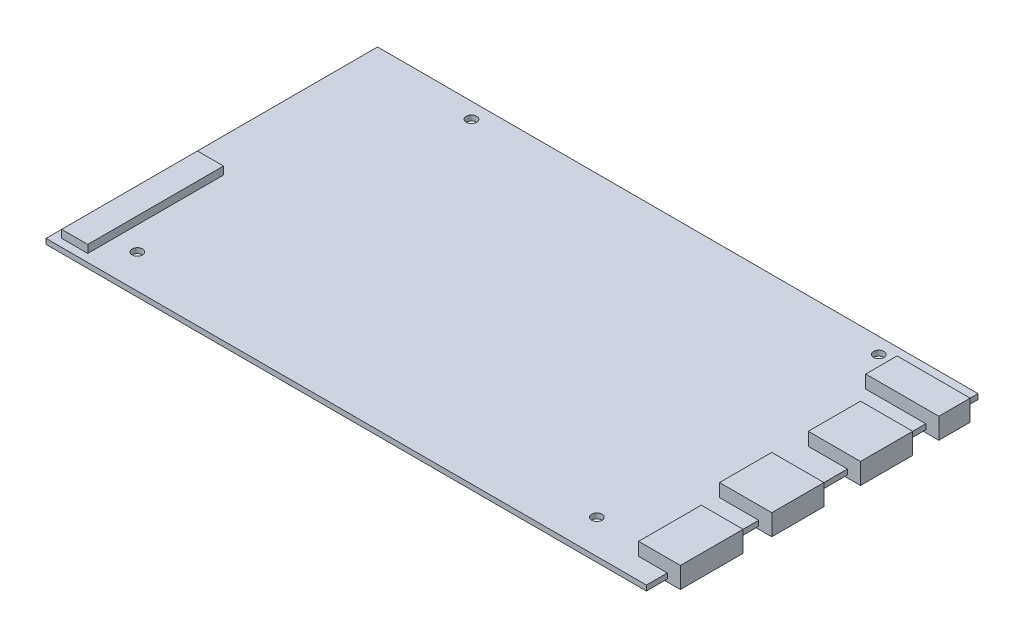
SolidWorks part; units mm, degrees
ref_plane "Front Plane" through (0, 0, 0) normal (0, 0, 1) x (1, 0, 0)
ref_plane "Top Plane" through (0, 0, 0) normal (0, 1, 0) x (1, 0, 0)
ref_plane "Right Plane" through (0, 0, 0) normal (1, 0, 0) x (0, 0, -1)
sketch "Sketch1" plane through (0, 0, 0) normal (0, 1, 0) x (1, 0, 0)
  line L1 (-57.5, 31.75) -> (57.5, 31.75)
  line L2 (-57.5, 31.75) -> (-57.5, -31.75)
  line L3 (-57.5, -31.75) -> (57.5, -31.75)
  line L4 (57.5, 31.75) -> (57.5, -31.75)
  line L5 (-57.5, 31.75) -> (57.5, -31.75) construction
  line L6 (-57.5, -31.75) -> (57.5, 31.75) construction
  circle A0 centre (-46.5, -25.25) radius 1
  circle A1 centre (-36.5, 28.75) radius 1
  circle A2 centre (41.5, 28.75) radius 1
  circle A3 centre (41.5, -25.25) radius 1
  point P0 (0, 0)
  dimension "D3" = 2
  dimension "D1" = 115
  dimension "D2" = 63.5
  dimension "D4" = 54
  dimension "D5" = 78
  dimension "D6" = 88
  dimension "D7" = 21
  dimension "D8" = 16
  dimension "D9" = 3
extrude "PCB" add sketch "Sketch1" along normal blind 1
sketch "Sketch2" plane through (0, 0, 0) normal (0, 1, 0) x (1, 0, 0)
  line L0 (-57.5, -31.75) -> (57.5, -31.75) construction
  line L1 (60, -27.75) -> (52, -27.75)
  line L2 (60, -27.75) -> (60, -15.75)
  line L3 (60, -15.75) -> (52, -15.75)
  line L4 (52, -27.75) -> (52, -15.75)
  line L5 (60, -10.25) -> (50, -10.25)
  line L6 (60, -10.25) -> (60, -0.25)
  line L7 (60, -0.25) -> (50, -0.25)
  line L8 (50, -10.25) -> (50, -0.25)
  line L9 (60, 6.75) -> (50, 6.75)
  line L10 (60, 6.75) -> (60, 16.75)
  line L11 (60, 16.75) -> (50, 16.75)
  line L12 (50, 6.75) -> (50, 16.75)
  line L13 (60, 27.75) -> (46, 27.75)
  line L14 (60, 27.75) -> (60, 21.75)
  line L15 (60, 21.75) -> (46, 21.75)
  line L16 (46, 27.75) -> (46, 21.75)
  line L17 (57.5, -31.75) -> (57.5, 31.75) construction
  line L18 (57.5, 31.75) -> (-57.5, 31.75) construction
  dimension "D1" = 4
  dimension "D2" = 16
  dimension "D3" = 2.5
  dimension "D4" = 8
  dimension "D5" = 21.5
  dimension "D6" = 31.5
  dimension "D7" = 10
  dimension "D8" = 25
  dimension "D9" = 15
  dimension "D10" = 4
  dimension "D11" = 10
  dimension "D12" = 14
extrude "CONNECTORS" add sketch "Sketch2" along normal blind 3.5 and the other way blind 0.5
sketch "Sketch3" plane through (0, 1, 0) normal (0, 1, 0) x (1, 0, 0)
  line L1 (-56, -30.25) -> (-51, -30.25)
  line L2 (-56, -30.25) -> (-56, -4.25)
  line L3 (-56, -4.25) -> (-51, -4.25)
  line L4 (-51, -30.25) -> (-51, -4.25)
  circle A0 centre (-46.5, -25.25) radius 1 construction
  point P4 (-51.1248, -3.7963)
  dimension "D1" = 5
  dimension "D2" = 26
  dimension "D3" = 4.5
  dimension "D4" = 5
extrude "DISPLAY CONNECTOR" add sketch "Sketch3" along normal blind 1.5
